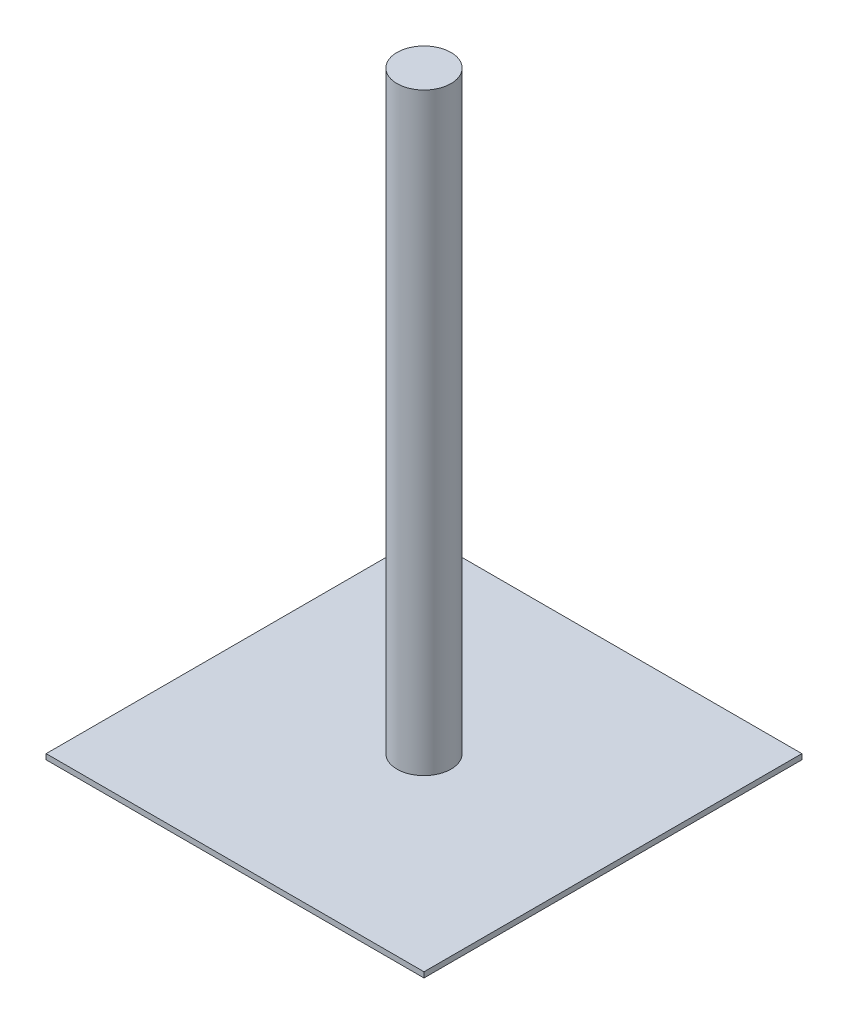
SolidWorks part; units mm, degrees
ref_plane "Front Plane" through (0, 0, 0) normal (0, 0, 1) x (1, 0, 0)
ref_plane "Top Plane" through (0, 0, 0) normal (0, 1, 0) x (1, 0, 0)
ref_plane "Right Plane" through (0, 0, 0) normal (1, 0, 0) x (0, 0, -1)
sketch "Sketch1" plane through (0, 0, 0) normal (0, 1, 0) x (1, 0, 0)
  line L1 (-350, -350) -> (350, -350)
  line L2 (-350, -350) -> (-350, 350)
  line L3 (-350, 350) -> (350, 350)
  line L4 (350, -350) -> (350, 350)
  line L5 (-350, -350) -> (350, 350) construction
  line L6 (-350, 350) -> (350, -350) construction
  point P0 (0, 0)
  dimension "D1" = 700
  dimension "D2" = 700
extrude "Boss-Extrude1" add sketch "Sketch1" along normal blind 10
sketch "Sketch3" plane through (0, 10, 0) normal (0, 1, 0) x (1, 0, 0)
  circle A0 centre (0, 0) radius 50
  dimension "D1" = 100
extrude "Boss-Extrude2" add sketch "Sketch3" along normal blind 1100
